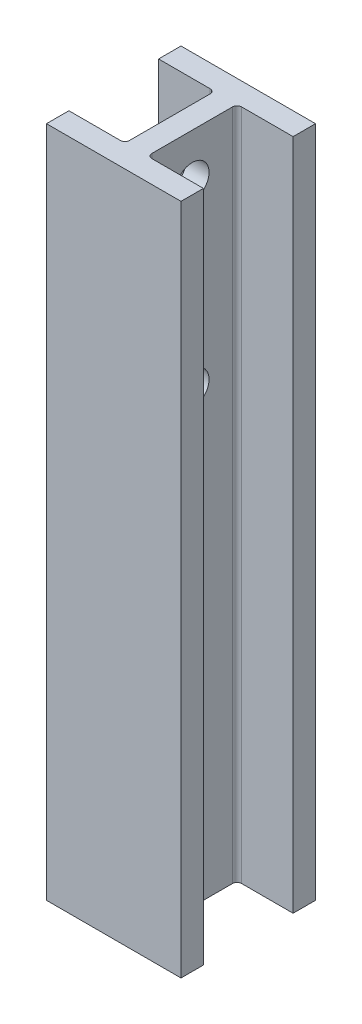
SolidWorks part; units mm, degrees
ref_plane "Front Plane" through (0, 0, 0) normal (0, 0, 1) x (1, 0, 0)
ref_plane "Top Plane" through (0, 0, 0) normal (0, 1, 0) x (1, 0, 0)
ref_plane "Right Plane" through (0, 0, 0) normal (1, 0, 0) x (0, 0, -1)
sketch "Sketch1" plane through (0, 0, 0) normal (0, 1, 0) x (1, 0, 0)
  line L0 (175, 50) -> (300, 50)
  line L1 (0, 0) -> (300, 0)
  line L2 (0, 0) -> (0, 50)
  line L3 (0, 50) -> (125, 50)
  line L4 (300, 0) -> (300, 50)
  line L6 (125, 50) -> (125, 250)
  line L8 (175, 50) -> (175, 250)
  line L9 (0, 250) -> (125, 250)
  line L10 (0, 250) -> (0, 300)
  line L11 (0, 300) -> (300, 300)
  line L12 (300, 250) -> (300, 300)
  line L13 (175, 250) -> (300, 250)
  dimension "D1" = 300
  dimension "D2" = 50
  dimension "D3" = 50
  dimension "D4" = 300
extrude "Boss-Extrude1" add sketch "Sketch1" along normal blind 1500
fillet "Fillet1" radius 10 4 edges at (125, 750, -250) (175, 750, -250) (175, 750, -50) (125, 750, -50)
sketch "Sketch2" plane through (125, 0, 0) normal (-1, 0, 0) x (0, 0, 1)
  line L0 (-150, 1500) -> (-150, 0) construction
  line L1 (-240, 1500) -> (-60, 1500) construction
  line L2 (-240, 0) -> (-60, 0) construction
  circle A0 centre (-150, 1400) radius 37.5
  circle A1 centre (-150, 1000) radius 37.5
  dimension "D1" = 75
  dimension "D2" = 100
  dimension "D3" = 400
extrude "Cut-Extrude1" cut sketch "Sketch2" against normal through all
